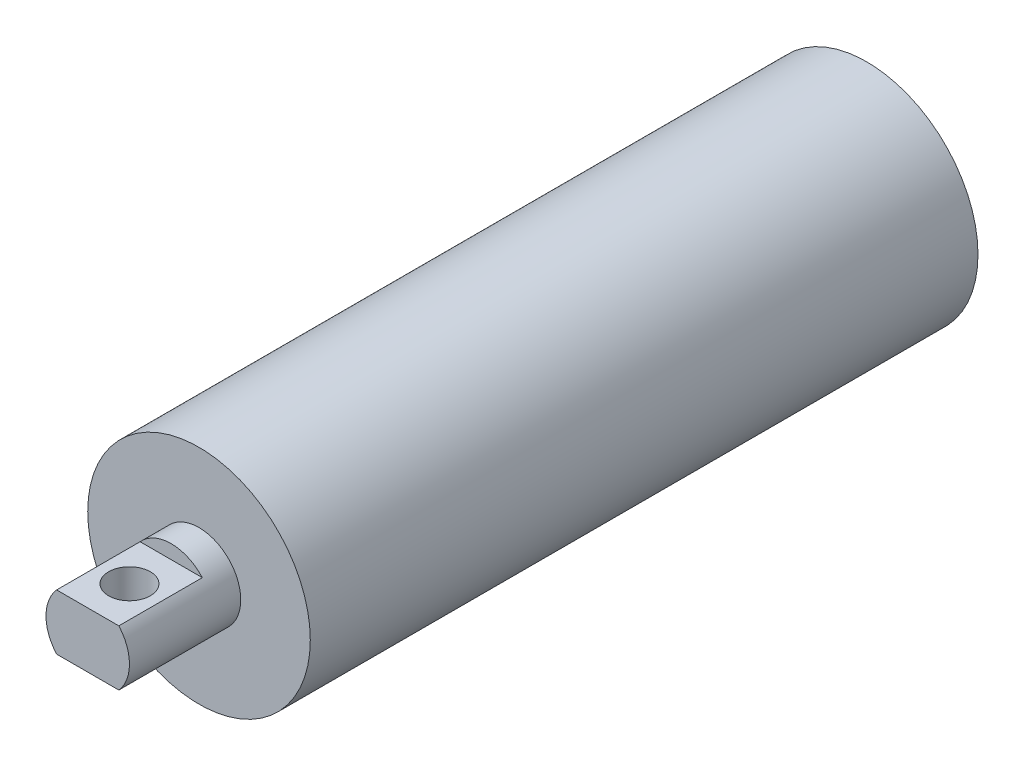
SolidWorks part; units mm, degrees
ref_plane "Front Plane" through (0, 0, 0) normal (0, 0, 1) x (1, 0, 0)
ref_plane "Top Plane" through (0, 0, 0) normal (0, 1, 0) x (1, 0, 0)
ref_plane "Right Plane" through (0, 0, 0) normal (1, 0, 0) x (0, 0, -1)
sketch "Sketch1" plane through (0, 0, 0) normal (0, 0, 1) x (1, 0, 0)
  circle A0 centre (0, 0) radius 25.4
  dimension "D1" = 50.8
extrude "Boss-Extrude1" add sketch "Sketch1" along normal blind 152.4
sketch "Sketch2" plane through (0, 0, 152.4) normal (0, 0, 1) x (1, 0, 0)
  circle A0 centre (0, 0) radius 9.525
  dimension "D1" = 19.05
extrude "Boss-Extrude2" add sketch "Sketch2" along normal blind 25.4
sketch "Sketch3" plane through (0, 0, 0) normal (0, 0, -1) x (-1, 0, 0)
  circle A0 centre (0, 0) radius 6.35
  dimension "D1" = 12.7
extrude "Cut-Extrude1" cut sketch "Sketch3" against normal blind 100.33
sketch "Sketch4" plane through (0, 0, 0) normal (1, 0, 0) x (0, 0, -1)
  line L0 (55, 0) -> (-55, 0) construction
  line L1 (-177.8, 9.525) -> (-158.75, 9.525)
  line L2 (-177.8, 9.525) -> (-177.8, 6.35)
  line L3 (-177.8, 6.35) -> (-158.75, 6.35)
  line L4 (-158.75, 9.525) -> (-158.75, 6.35)
  line L5 (-177.8, -9.525) -> (-158.75, -9.525)
  line L6 (-177.8, -9.525) -> (-177.8, -6.35)
  line L7 (-177.8, -6.35) -> (-158.75, -6.35)
  line L8 (-158.75, -9.525) -> (-158.75, -6.35)
  dimension "D1" = 19.05
  dimension "D2" = 19.05
  dimension "D3" = 6.35
  dimension "D4" = 6.35
extrude "Cut-Extrude2" cut sketch "Sketch4" against normal through all both and the other way through all
sketch "Sketch5" plane through (0, -6.35, 0) normal (0, -1, 0) x (1, 0, 0)
  line L0 (0, -55) -> (0, 55) construction
  line L1 (7.0995, 177.8) -> (-7.0995, 177.8) construction
  circle A0 centre (0, 168.275) radius 4.7625
  dimension "D1" = 9.525
  dimension "D2" = 9.525
extrude "Cut-Extrude3" cut sketch "Sketch5" against normal through all both
equation "\"D2@Sketch4\"=\"D1@Sketch4\""
